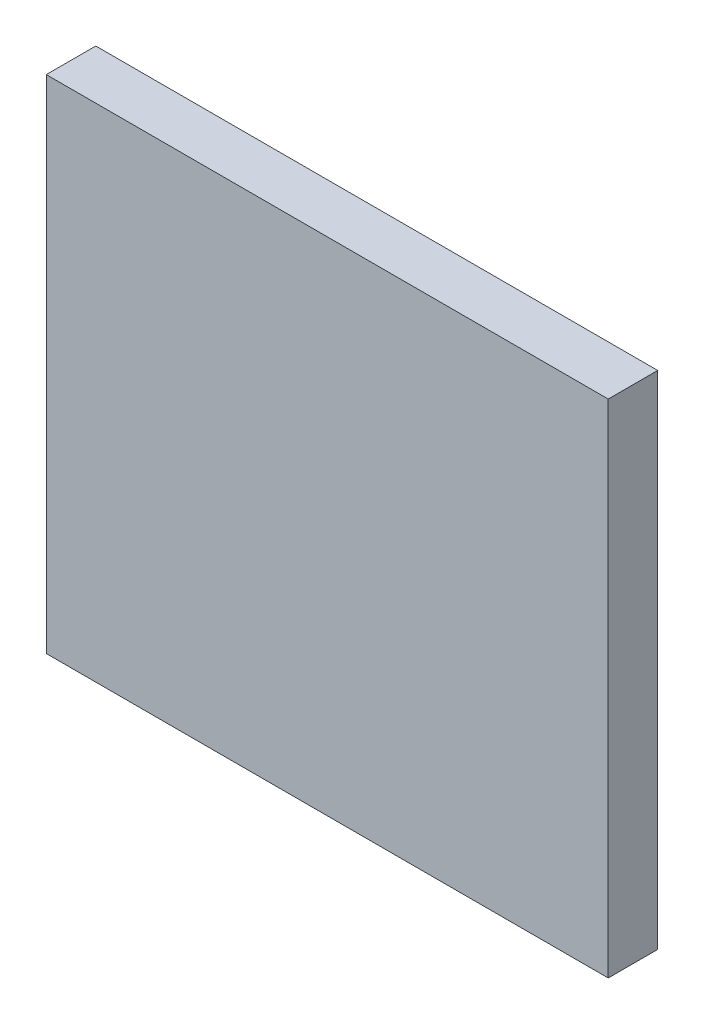
SolidWorks part; units mm, degrees
ref_plane "Front Plane" through (0, 0, 0) normal (0, 0, 1) x (1, 0, 0)
ref_plane "Top Plane" through (0, 0, 0) normal (0, 1, 0) x (1, 0, 0)
ref_plane "Right Plane" through (0, 0, 0) normal (1, 0, 0) x (0, 0, -1)
sketch "Sketch1" plane through (0, 0, 0) normal (0, 0, 1) x (1, 0, 0)
  line L0 (-6.35, 1.3135) -> (5, 1.3135)
  line L1 (5, 1.3135) -> (5, -8.8135)
  line L2 (5, -8.8135) -> (-6.35, -8.8135)
  line L3 (-6.35, -8.8135) -> (-6.35, 1.3135)
extrude "Component_Outline" add sketch "Sketch1" along normal blind 1 separate body
sketch3d "3DSketch1"
  line L0 (0, 0, 0) -> (1, 0, 0)
  line L1 (0, 0, 0) -> (0, 1, 0)
  line L2 (0, 0, 0) -> (0, 0, 1)
  point P0 (0, 0, 0)
